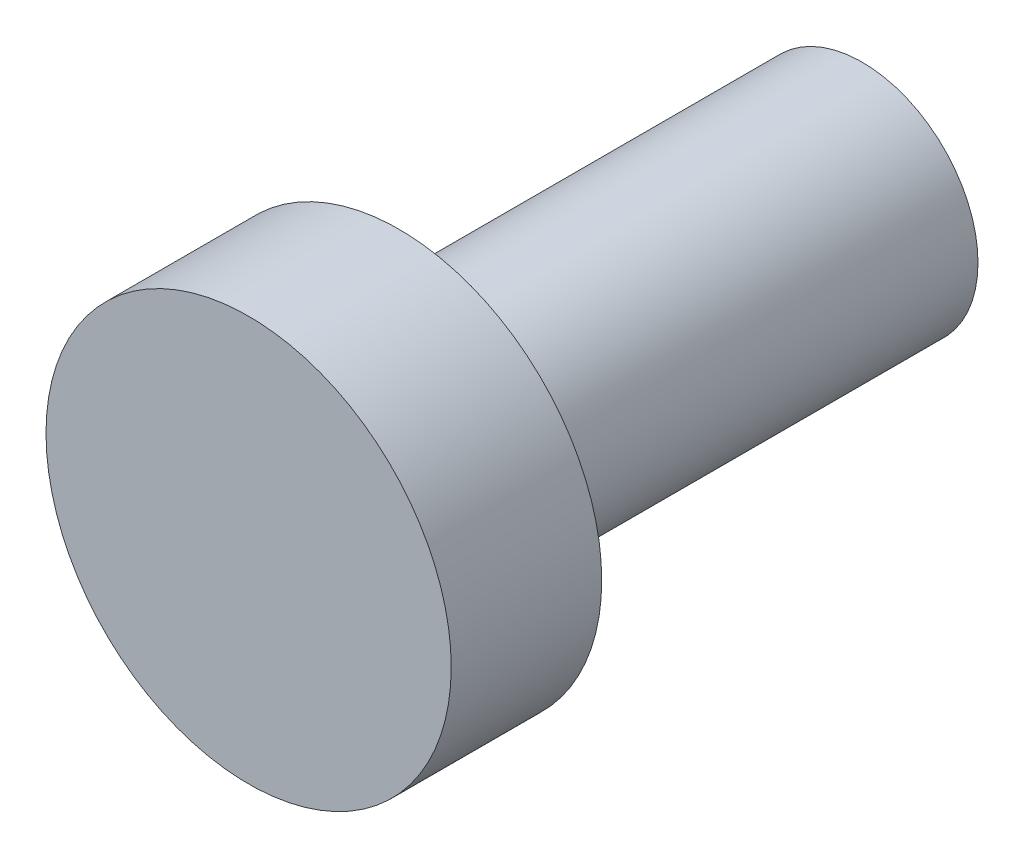
SolidWorks part; units mm, degrees
material "AISI 4340 Steel, normalized"
ref_plane "Front Plane" through (0, 0, 0) normal (0, 0, 1) x (1, 0, 0)
ref_plane "Top Plane" through (0, 0, 0) normal (0, 1, 0) x (1, 0, 0)
ref_plane "Right Plane" through (0, 0, 0) normal (1, 0, 0) x (0, 0, -1)
sketch "Sketch1" plane through (0, 0, 0) normal (0, 0, 1) x (1, 0, 0)
  circle A0 centre (0, 0) radius 1.75
extrude "Conservative_Button_Head_Envelope" add sketch "Sketch1" along normal blind 1.3
sketch "Sketch2" plane through (0, 0, 0) normal (0, 0, 1) x (1, 0, 0)
  circle A0 centre (0, 0) radius 1
extrude "M2x0p4x4_Thread_Major_Envelope" add sketch "Sketch2" along normal blind 4 from offset 4
